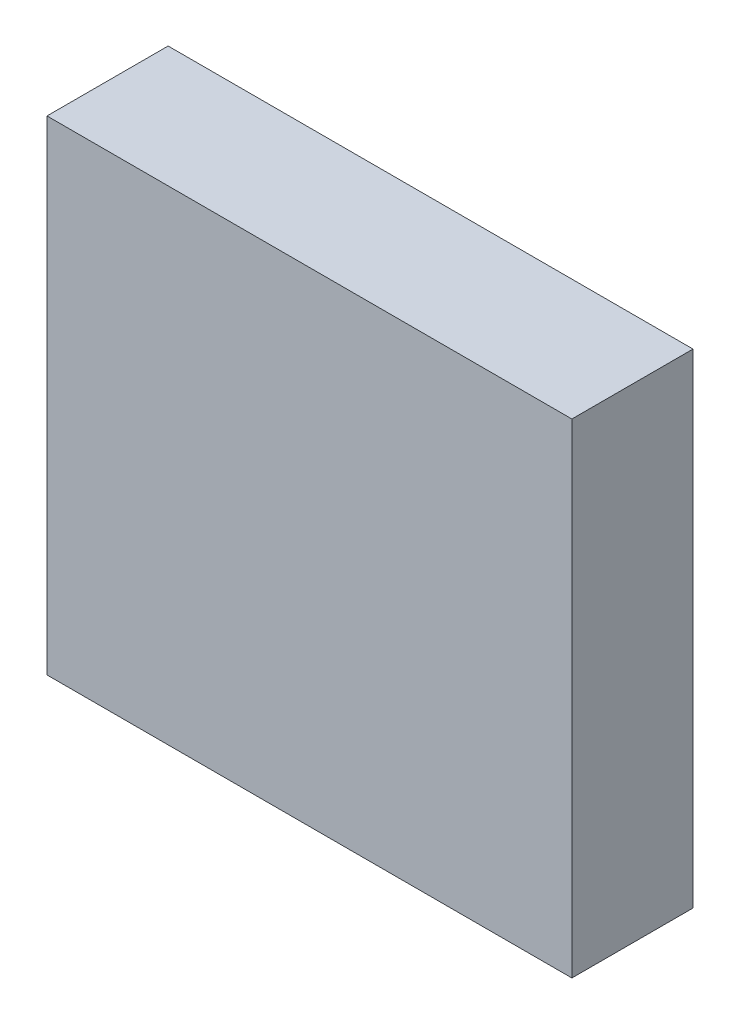
SolidWorks part; units mm, degrees
material "Polyurethane Foam Rigid"
ref_plane "X-Y Datum" through (0, 0, 0) normal (0, 0, 1) x (1, 0, 0)
ref_plane "X-Z Datum" through (0, 0, 0) normal (0, 1, 0) x (1, 0, 0)
ref_plane "Y-Z Datum" through (0, 0, 0) normal (1, 0, 0) x (0, 0, -1)
sketch "Sketch1" plane through (0, 0, 0) normal (0, 0, 1) x (1, 0, 0)
  line L1 (-82.55, -76.1378) -> (82.55, -76.1378)
  line L2 (-82.55, -76.1378) -> (-82.55, 76.1378)
  line L3 (-82.55, 76.1378) -> (82.55, 76.1378)
  line L4 (82.55, -76.1378) -> (82.55, 76.1378)
  line L5 (-82.55, -76.1378) -> (82.55, 76.1378) construction
  line L6 (-82.55, 76.1378) -> (82.55, -76.1378) construction
  point P0 (0, 0)
  dimension "D1" = 152.2755
  dimension "D2" = 165.1
extrude "Boss-Extrude1" add sketch "Sketch1" along normal blind 38.1
